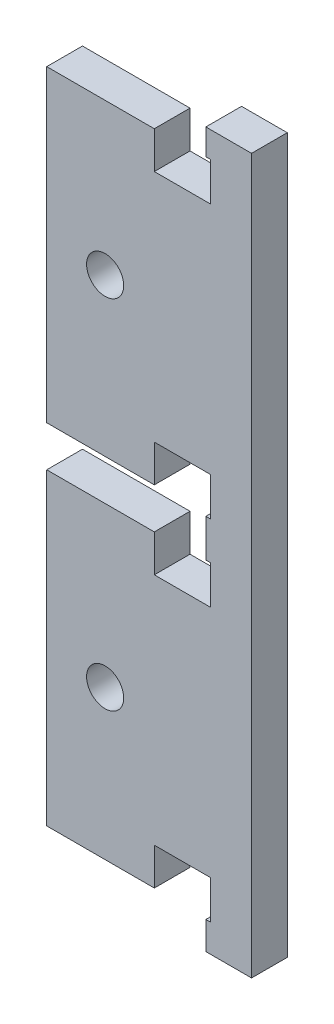
SolidWorks part; units mm, degrees
material "AISI 4130 Steel, annealed at 865C"
ref_plane "X-Y Datum" through (0, 0, 0) normal (0, 0, 1) x (1, 0, 0)
ref_plane "X-Z Datum" through (0, 0, 0) normal (0, 1, 0) x (1, 0, 0)
ref_plane "Y-Z Datum" through (0, 0, 0) normal (1, 0, 0) x (0, 0, -1)
sketch "Sketch2" plane through (0, 0, 0) normal (0, 0, 1) x (1, 0, 0)
  line L0 (-332.3254, 135.7857) -> (-332.3254, 326.2217) construction
  line L1 (-316.4504, 135.7857) -> (-348.2004, 135.7857) construction
  line L2 (-316.4504, 326.2217) -> (-348.2004, 326.2217) construction
  line L4 (-348.2004, 135.7857) -> (-306.2904, 135.7857)
  line L5 (-348.2004, 135.7857) -> (-348.2004, 326.2217)
  line L6 (-348.2004, 326.2217) -> (-306.2904, 326.2217)
  line L7 (-306.2904, 135.7857) -> (-306.2904, 326.2217)
  dimension "D1" = 41.91
extrude "Boss-Extrude1" add sketch "Sketch2" along normal blind 6.35
sketch "Sketch3" plane through (0, 0, 6.35) normal (0, 0, 1) x (1, 0, 0)
  line L0 (-316.4504, 326.2217) -> (-348.2004, 326.2217) construction
  line L1 (-348.2004, 326.2217) -> (-348.2004, 323.0467) construction
  line L2 (-348.2004, 323.0467) -> (-316.4504, 323.0467) construction
  line L3 (-316.4504, 323.0467) -> (-316.4504, 326.2217) construction
  line L4 (-316.4504, 259.9597) -> (-316.4504, 263.1347) construction
  line L5 (-316.4504, 263.1347) -> (-348.2004, 263.1347) construction
  line L6 (-348.2004, 263.1347) -> (-348.2004, 259.9597) construction
  line L7 (-348.2004, 259.9597) -> (-316.4504, 259.9597) construction
  line L8 (-316.4504, 197.8727) -> (-316.4504, 201.0477) construction
  line L9 (-316.4504, 201.0477) -> (-348.2004, 201.0477) construction
  line L10 (-348.2004, 201.0477) -> (-348.2004, 197.8727) construction
  line L11 (-348.2004, 197.8727) -> (-316.4504, 197.8727) construction
  line L12 (-316.4504, 135.7857) -> (-316.4504, 138.9607) construction
  line L13 (-316.4504, 138.9607) -> (-348.2004, 138.9607) construction
  line L14 (-348.2004, 138.9607) -> (-348.2004, 135.7857) construction
  line L15 (-348.2004, 135.7857) -> (-316.4504, 135.7857) construction
  line L16 (-316.4504, 326.2217) -> (-348.2004, 326.2217) construction
  line L17 (-348.2004, 326.2217) -> (-348.2004, 323.0467) construction
  line L18 (-348.2004, 323.0467) -> (-316.4504, 323.0467) construction
  line L19 (-316.4504, 323.0467) -> (-316.4504, 326.2217) construction
  line L20 (-316.4504, 259.9597) -> (-316.4504, 263.1347) construction
  line L21 (-316.4504, 263.1347) -> (-348.2004, 263.1347) construction
  line L22 (-348.2004, 263.1347) -> (-348.2004, 259.9597) construction
  line L23 (-348.2004, 259.9597) -> (-316.4504, 259.9597) construction
  line L24 (-316.4504, 197.8727) -> (-316.4504, 201.0477)
  line L25 (-316.4504, 201.0477) -> (-348.2004, 201.0477) construction
  line L26 (-348.2004, 201.0477) -> (-348.2004, 197.8727) construction
  line L27 (-348.2004, 197.8727) -> (-316.4504, 197.8727) construction
  line L28 (-316.4504, 135.7857) -> (-316.4504, 138.9607) construction
  line L29 (-316.4504, 138.9607) -> (-348.2004, 138.9607) construction
  line L30 (-348.2004, 138.9607) -> (-348.2004, 135.7857) construction
  line L31 (-348.2004, 135.7857) -> (-316.4504, 135.7857) construction
  line L32 (-314.4184, 140.9927) -> (-350.2324, 140.9927)
  line L33 (-350.2324, 140.9927) -> (-350.2324, 133.7537)
  line L34 (-350.2324, 133.7537) -> (-314.4184, 133.7537)
  line L35 (-314.4184, 133.7537) -> (-314.4184, 140.9927)
  line L36 (-314.4184, 203.0797) -> (-350.2324, 203.0797)
  line L37 (-350.2324, 203.0797) -> (-350.2324, 195.8407)
  line L38 (-350.2324, 195.8407) -> (-314.4184, 195.8407)
  line L39 (-314.4184, 195.8407) -> (-314.4184, 203.0797)
  line L40 (-314.4184, 265.1667) -> (-350.2324, 265.1667)
  line L41 (-350.2324, 265.1667) -> (-350.2324, 257.9277)
  line L42 (-350.2324, 257.9277) -> (-314.4184, 257.9277)
  line L43 (-314.4184, 257.9277) -> (-314.4184, 265.1667)
  line L44 (-350.2324, 321.0147) -> (-314.4184, 321.0147)
  line L45 (-314.4184, 321.0147) -> (-314.4184, 328.2537)
  line L46 (-314.4184, 328.2537) -> (-350.2324, 328.2537)
  line L47 (-350.2324, 328.2537) -> (-350.2324, 321.0147)
  line L50 (-342.7084, 326.2217) -> (-342.7084, 135.7857)
  line L51 (-342.7084, 326.2217) -> (-342.7084, 135.7857)
  circle A0 centre (-332.3254, 294.5357) radius 3.3 construction
  circle A1 centre (-332.3254, 231.0357) radius 3.3 construction
  circle A2 centre (-332.3254, 167.5357) radius 3.3 construction
  circle A3 centre (-332.3254, 294.5357) radius 3.3
  circle A4 centre (-332.3254, 231.0357) radius 3.3
  circle A5 centre (-332.3254, 167.5357) radius 3.3
  line M12 (-348.2004, 326.2217) -> (-348.2004, 135.7857)
  line M13 (-348.2004, 135.7857) -> (-306.2904, 135.7857)
  line M15 (-306.2904, 326.2217) -> (-348.2004, 326.2217)
  dimension "D1" = 2.032
  dimension "D2" = 5.492
extrude "Cut-Extrude1" cut sketch "Sketch3" against normal through all contours L35 L32 L29 L28 M13 M12 | L34 L35 L32 L33 M13 M12 | L28 L29 M12 M13 | L27 L24 L25 M12 | L38 L39 L36 L25 L24 L27 M12 | L23 L20 L21 M12 | L42 L43 L40 L21 L20 L23 M12 | L18 L19 M15 M12 | L44 L45 L19 L18 M15 M12 | L46 L47 L44 L45 M12 M15 | L41 L42 L40 M12 | L37 L38 L36 M12 | A5 | A4 | A3 | L51 L38 L32 M12 | L51 L42 L36 M12 | L51 L44 L40 M12
sketch "Sketch4" plane through (0, 0, 6.35) normal (0, 0, 1) x (1, 0, 0)
  line L0 (-313.8025, 140.9927) -> (-313.8025, 147.3427) construction
  line L1 (-323.3275, 140.9927) -> (-323.3275, 147.3427) construction
  line L2 (-313.8025, 189.4813) -> (-313.8025, 195.8313) construction
  line L3 (-323.3275, 189.4813) -> (-323.3275, 195.8313) construction
  line L4 (-313.8025, 203.0703) -> (-313.8025, 209.4203) construction
  line L5 (-323.3275, 203.0703) -> (-323.3275, 209.4203) construction
  line L6 (-313.8025, 251.5843) -> (-313.8025, 257.9343) construction
  line L7 (-323.3275, 251.5843) -> (-323.3275, 257.9343) construction
  line L8 (-323.3275, 265.1733) -> (-323.3275, 271.5233) construction
  line L9 (-313.8025, 265.1733) -> (-313.8025, 271.5233) construction
  line L10 (-323.3275, 314.6779) -> (-323.3275, 321.0279) construction
  line L11 (-313.8025, 314.6779) -> (-313.8025, 321.0279) construction
  line L12 (-313.8025, 140.9927) -> (-313.8025, 147.3427) construction
  line L13 (-323.3275, 140.9927) -> (-323.3275, 147.3427) construction
  line L14 (-313.8025, 189.4813) -> (-313.8025, 195.8313) construction
  line L15 (-323.3275, 189.4813) -> (-323.3275, 195.8313) construction
  line L16 (-313.8025, 203.0703) -> (-313.8025, 209.4203) construction
  line L17 (-323.3275, 203.0703) -> (-323.3275, 209.4203) construction
  line L18 (-313.8025, 251.5843) -> (-313.8025, 257.9343) construction
  line L19 (-323.3275, 251.5843) -> (-323.3275, 257.9343) construction
  line L20 (-323.3275, 265.1733) -> (-323.3275, 271.5233) construction
  line L21 (-313.8025, 265.1733) -> (-313.8025, 271.5233) construction
  line L22 (-323.3275, 314.6779) -> (-323.3275, 321.0279) construction
  line L23 (-313.8025, 314.6779) -> (-313.8025, 321.0279) construction
  line L24 (-333.1834, 314.6779) -> (-288.5206, 314.6779) construction
  line L25 (-288.5206, 321.0279) -> (-333.1834, 321.0279) construction
  line L26 (-333.1834, 140.9927) -> (-288.5206, 140.9927) construction
  line L27 (-288.5206, 147.3427) -> (-333.1834, 147.3427) construction
  line L28 (-333.1834, 189.4813) -> (-288.5206, 189.4813) construction
  line L29 (-288.5206, 195.8313) -> (-333.1834, 195.8313) construction
  line L30 (-333.1834, 203.0703) -> (-288.5206, 203.0703) construction
  line L31 (-288.5206, 209.4203) -> (-333.1834, 209.4203) construction
  line L32 (-333.1834, 251.5843) -> (-288.5206, 251.5843) construction
  line L33 (-288.5206, 257.9343) -> (-333.1834, 257.9343) construction
  line L34 (-333.1834, 265.1733) -> (-288.5206, 265.1733) construction
  line L35 (-288.5206, 271.5233) -> (-333.1834, 271.5233) construction
  line L36 (-323.3275, 140.9927) -> (-313.8025, 140.9927) construction
  line L37 (-313.8025, 147.3427) -> (-323.3275, 147.3427) construction
  line L38 (-323.3275, 189.4813) -> (-313.8025, 189.4813) construction
  line L39 (-313.8025, 195.8313) -> (-323.3275, 195.8313) construction
  line L40 (-323.3275, 203.0703) -> (-313.8025, 203.0703) construction
  line L41 (-313.8025, 209.4203) -> (-323.3275, 209.4203) construction
  line L42 (-323.3275, 251.5843) -> (-313.8025, 251.5843) construction
  line L43 (-313.8025, 257.9343) -> (-323.3275, 257.9343) construction
  line L44 (-323.3275, 265.1733) -> (-313.8025, 265.1733) construction
  line L45 (-313.8025, 271.5233) -> (-323.3275, 271.5233) construction
  line L46 (-313.8025, 321.0279) -> (-323.3275, 321.0279) construction
  line L47 (-323.3275, 314.6779) -> (-313.8025, 314.6779) construction
  line L48 (-313.5485, 140.7387) -> (-313.5485, 147.5967)
  line L49 (-313.5485, 147.5967) -> (-323.5815, 147.5967)
  line L50 (-323.5815, 140.7387) -> (-323.5815, 147.5967)
  line L51 (-323.5815, 140.7387) -> (-313.5485, 140.7387)
  line L52 (-313.5485, 189.2273) -> (-313.5485, 196.0853)
  line L53 (-313.5485, 196.0853) -> (-323.5815, 196.0853)
  line L54 (-323.5815, 189.2273) -> (-323.5815, 196.0853)
  line L55 (-323.5815, 189.2273) -> (-313.5485, 189.2273)
  line L56 (-313.5485, 202.8163) -> (-313.5485, 209.6743)
  line L57 (-313.5485, 209.6743) -> (-323.5815, 209.6743)
  line L58 (-323.5815, 202.8163) -> (-323.5815, 209.6743)
  line L59 (-323.5815, 202.8163) -> (-313.5485, 202.8163)
  line L60 (-313.5485, 251.3303) -> (-313.5485, 258.1883)
  line L61 (-313.5485, 258.1883) -> (-323.5815, 258.1883)
  line L62 (-323.5815, 251.3303) -> (-323.5815, 258.1883)
  line L63 (-323.5815, 251.3303) -> (-313.5485, 251.3303)
  line L64 (-323.5815, 264.9193) -> (-323.5815, 271.7773)
  line L65 (-313.5485, 271.7773) -> (-323.5815, 271.7773)
  line L66 (-313.5485, 264.9193) -> (-313.5485, 271.7773)
  line L67 (-323.5815, 264.9193) -> (-313.5485, 264.9193)
  line L68 (-323.5815, 314.4239) -> (-323.5815, 321.2819)
  line L69 (-313.5485, 321.2819) -> (-323.5815, 321.2819)
  line L70 (-313.5485, 314.4239) -> (-313.5485, 321.2819)
  line L71 (-323.5815, 314.4239) -> (-313.5485, 314.4239)
  line M4 (-342.7084, 140.9927) -> (-314.4184, 140.9927)
  line M9 (-314.4184, 326.2217) -> (-314.4184, 321.0147)
  line M10 (-314.4184, 321.0147) -> (-342.7084, 321.0147)
  line M13 (-314.4184, 265.1667) -> (-314.4184, 257.9277)
  line M14 (-314.4184, 257.9277) -> (-342.7084, 257.9277)
  line M16 (-342.7084, 203.0797) -> (-314.4184, 203.0797)
  line M17 (-314.4184, 203.0797) -> (-314.4184, 195.8407)
  dimension "D1" = 0.254
extrude "Cut-Extrude2" cut sketch "Sketch4" against normal through all contours L12 L37 L13 L36 M4 | L14 L39 L15 L38 | L16 L41 L17 L40 M16 M17 | L18 L43 L19 L42 M13 M14 | L21 L45 L20 L44 | L22 L47 L23 L46 M9 M10
sketch "Sketch5" plane through (0, 0, 6.35) normal (0, 0, 1) x (1, 0, 0)
  line L0 (-314.4184, 262.7857) -> (-306.2904, 262.7857)
  line L1 (-314.4184, 258.1883) -> (-314.4184, 264.9193) construction
  line L2 (-306.2904, 135.7857) -> (-306.2904, 326.2217) construction
  circle M3 centre (-332.3254, 294.5357) radius 3.3
  line M11 (-306.2904, 135.7857) -> (-306.2904, 326.2217)
  line M12 (-306.2904, 326.2217) -> (-314.4184, 326.2217)
  line M13 (-314.4184, 326.2217) -> (-314.4184, 321.2819)
  line M14 (-314.4184, 321.2819) -> (-313.5485, 321.2819)
  line M15 (-313.5485, 321.2819) -> (-313.5485, 314.4239)
  line M16 (-313.5485, 314.4239) -> (-323.5815, 314.4239)
  line M17 (-323.5815, 314.4239) -> (-323.5815, 321.0147)
  line M18 (-323.5815, 321.0147) -> (-342.7084, 321.0147)
  line M19 (-342.7084, 321.0147) -> (-342.7084, 265.1667)
  line M20 (-342.7084, 265.1667) -> (-323.5815, 265.1667)
  line M21 (-323.5815, 265.1667) -> (-323.5815, 271.7773)
  line M22 (-323.5815, 271.7773) -> (-313.5485, 271.7773)
  line M23 (-313.5485, 271.7773) -> (-313.5485, 264.9193)
  line M24 (-313.5485, 264.9193) -> (-314.4184, 264.9193)
  line M25 (-314.4184, 264.9193) -> (-314.4184, 258.1883)
extrude "Cut-Extrude3" cut sketch "Sketch5" against normal through all and the other way through all contours L0 M25 M11 M12 M13 M14 M15 M16 M17 M18 M19 M20 M21 M22 M23 M24 M3
